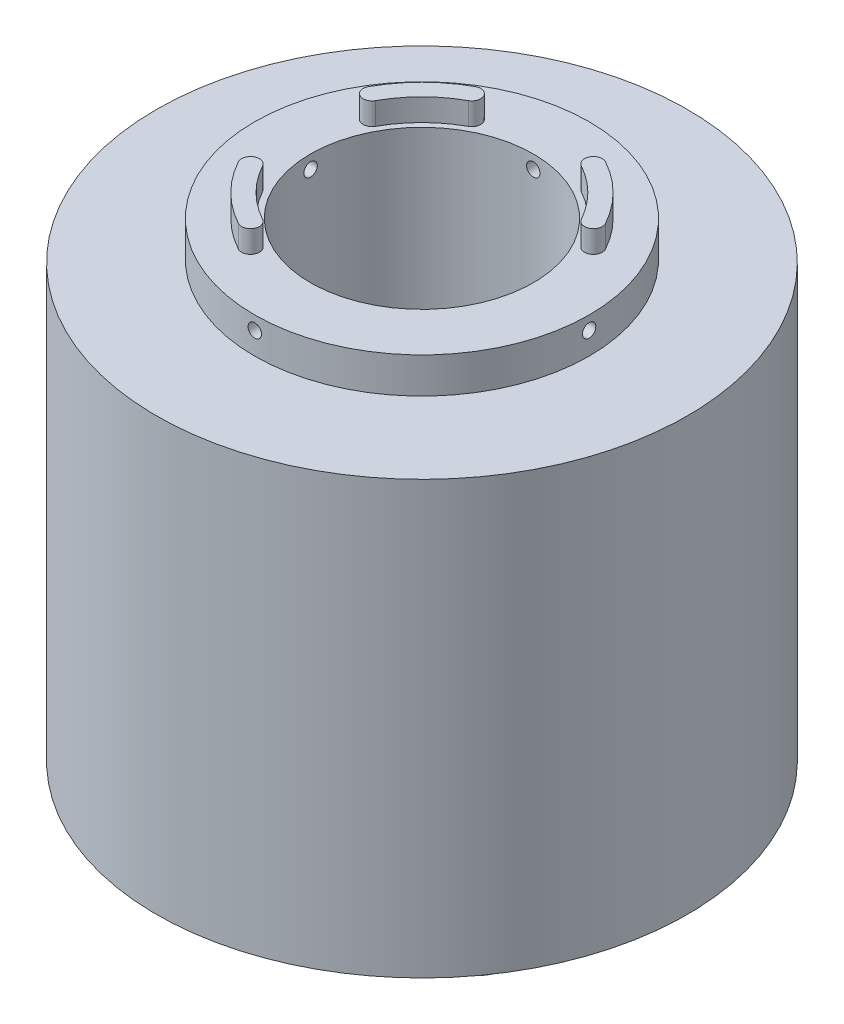
SolidWorks part; units mm, degrees
ref_plane "前视基准面" through (0, 0, 0) normal (0, 0, 1) x (1, 0, 0)
ref_plane "上视基准面" through (0, 0, 0) normal (0, 1, 0) x (1, 0, 0)
ref_plane "右视基准面" through (0, 0, 0) normal (1, 0, 0) x (0, 0, -1)
sketch "草图1" plane through (0, 0, 0) normal (0, 0, 1) x (1, 0, 0)
  line L0 (0, 57) -> (0, -48.4)
  line L1 (59.5, 48.4) -> (25, 48.4)
  line L2 (59.5, 48.4) -> (59.5, -48.4)
  line L3 (59.5, -48.4) -> (-59.5, -48.4)
  line L4 (-59.5, 48.4) -> (-59.5, -48.4)
  line L5 (59.5, 48.4) -> (-59.5, -48.4) construction
  line L6 (59.5, -48.4) -> (-59.5, 48.4) construction
  line L8 (25, 48.4) -> (25, -48.4)
  line L9 (25, -48.4) -> (-25, -48.4)
  line L10 (-25, 48.4) -> (-25, -48.4)
  line L11 (25, 48.4) -> (-25, -48.4) construction
  line L12 (25, -48.4) -> (-25, 48.4) construction
  line L13 (-25, 48.4) -> (-59.5, 48.4)
  line L18 (-37.5, 49) -> (37.5, 49)
  line L19 (-32.5, 49) -> (-32.5, 48.4)
  line L20 (37.5, 57) -> (-37.5, 57)
  line L21 (37.5, 57) -> (37.5, 49)
  line L23 (-37.5, 57) -> (-37.5, 49)
  line L24 (-25, 48.4) -> (-25, 57)
  point P0 (0, 0)
  point P5 (0, 0)
  dimension "D1" = 119
  dimension "D2" = 50
  dimension "D3" = 96.8
  dimension "D4" = 8.6
  dimension "D5" = 8
  dimension "D6" = 75
  dimension "D7" = 5
revolve "旋转1" add sketch "草图1" angle 360 about L0
sketch "草图3" plane through (0, 0, 0) normal (0, 0, 1) x (1, 0, 0)
  line L0 (37.5, 57) -> (-37.5, 57) construction
  circle A0 centre (0, 54) radius 1.5
  dimension "D1" = 3
  dimension "D2" = 3
extrude "切除-拉伸1" cut sketch "草图3" against normal through all
pattern_circular "阵列(圆周)1" count 4 over 360 about axis through (0, 57, 0) along (0, 1, 0) of "切除-拉伸1"
sketch "草图4" plane through (0, -48.4, 0) normal (0, -1, 0) x (1, 0, 0)
  line L5 (-0.4176, 62.7684) -> (0.2776, 64.3102) construction
  line L8 (0.2776, 64.3102) -> (0.4176, 62.7684) construction
  line L10 (63.47, 0) -> (-63.47, 0) construction
  line L19 (0, 59.5) -> (0, 0) construction
  circle A3 centre (-6.25, 51.75) radius 2
  circle A4 centre (0, 0) radius 59.5 construction
  circle A5 centre (6.25, 51.75) radius 2
  circle A6 centre (-6.25, -51.75) radius 2
  circle A7 centre (6.25, -51.75) radius 2
  point P0 (0.2776, 64.3102)
  dimension "D2" = 103.5
  dimension "D6" = 4
  dimension "D1" = 6.25
sketch "草图5" plane through (0, 57, 0) normal (0, 1, 0) x (1, 0, 0)
  line L0 (0, 0) -> (21.4253, 21.4253) construction
  line L2 (0, 0) -> (25, 0) construction
  line L3 (13.6295, 24.8018) -> (24.8018, 13.6295) construction
  arc A14 (14.5927, 26.5545) -> (26.5545, 14.5927) centre (0, 0) cw
  arc A15 (26.5545, 14.5927) -> (23.049, 12.6663) centre (24.8018, 13.6295) cw
  circle A19 centre (0, 0) radius 25 construction
  arc A33 (12.6663, 23.049) -> (14.5927, 26.5545) centre (13.6295, 24.8018) cw
  arc A34 (12.6663, 23.049) -> (23.049, 12.6663) centre (0, 0) cw
  arc A39 (-26.5545, -14.5927) -> (-23.049, -12.6663) centre (-24.8018, -13.6295) cw
  arc A40 (-14.5927, -26.5545) -> (-26.5545, -14.5927) centre (0, 0) cw
  arc A41 (-12.6663, -23.049) -> (-23.049, -12.6663) centre (0, 0) cw
  arc A42 (-12.6663, -23.049) -> (-14.5927, -26.5545) centre (-13.6295, -24.8018) cw
  arc A43 (-14.5927, 26.5545) -> (-12.6663, 23.049) centre (-13.6295, 24.8018) cw
  arc A44 (-26.5545, 14.5927) -> (-14.5927, 26.5545) centre (0, 0) cw
  arc A45 (-23.049, 12.6663) -> (-12.6663, 23.049) centre (0, 0) cw
  arc A46 (-23.049, 12.6663) -> (-26.5545, 14.5927) centre (-24.8018, 13.6295) cw
  arc A47 (14.5927, -26.5545) -> (12.6663, -23.049) centre (13.6295, -24.8018) cw [skipped]
  arc A48 (26.5545, -14.5927) -> (14.5927, -26.5545) centre (0, 0) cw [skipped]
  arc A49 (23.049, -12.6663) -> (12.6663, -23.049) centre (0, 0) cw [skipped]
  arc A50 (23.049, -12.6663) -> (26.5545, -14.5927) centre (24.8018, -13.6295) cw [skipped]
  point P6 (17.6777, 17.6777)
  point P11 (19.2156, 19.2156)
  point P35 (0, 0)
  point P37 (0, 0)
  dimension "D1" = 2
  dimension "D3" = 15.8
  dimension "D4" = 5.3
  dimension "D2" = 45
extrude "凸台-拉伸2" add sketch "草图5" along normal blind 5
sketch "草图6" plane through (0, -48.4, 0) normal (0, -1, 0) x (1, 0, 0)
  line L0 (40.6852, 27.5311) -> (44.1852, 21.4689) construction
  line L1 (43.7163, 29.2811) -> (47.2163, 23.2189)
  line L2 (37.6542, 25.7811) -> (41.1542, 19.7189)
  line L3 (0, 0) -> (-59.5, 0) construction
  line L4 (40.6852, -27.5311) -> (44.1852, -21.4689) construction
  line L5 (42.4352, 24.5) -> (0, 0) construction
  line L6 (43.7163, -29.2811) -> (47.2163, -23.2189)
  line L7 (37.6542, -25.7811) -> (41.1542, -19.7189)
  line L8 (0, -63.47) -> (0, 63.47) construction
  line L9 (-40.6852, -27.5311) -> (-44.1852, -21.4689) construction
  line L10 (-43.7163, -29.2811) -> (-47.2163, -23.2189)
  line L11 (-37.6542, -25.7811) -> (-41.1542, -19.7189)
  line L12 (-40.6852, 27.5311) -> (-44.1852, 21.4689) construction
  line L13 (-43.7163, 29.2811) -> (-47.2163, 23.2189)
  line L14 (-37.6542, 25.7811) -> (-41.1542, 19.7189)
  arc A0 (43.7163, 29.2811) -> (37.6542, 25.7811) centre (40.6852, 27.5311) ccw
  arc A1 (41.1542, 19.7189) -> (47.2163, 23.2189) centre (44.1852, 21.4689) ccw
  circle A2 centre (0, 0) radius 59.5 construction
  arc A4 (43.7163, -29.2811) -> (37.6542, -25.7811) centre (40.6852, -27.5311) cw
  arc A5 (41.1542, -19.7189) -> (47.2163, -23.2189) centre (44.1852, -21.4689) cw
  arc A6 (-43.7163, -29.2811) -> (-37.6542, -25.7811) centre (-40.6852, -27.5311) ccw
  arc A7 (-41.1542, -19.7189) -> (-47.2163, -23.2189) centre (-44.1852, -21.4689) ccw
  arc A8 (-43.7163, 29.2811) -> (-37.6542, 25.7811) centre (-40.6852, 27.5311) cw
  arc A9 (-41.1542, 19.7189) -> (-47.2163, 23.2189) centre (-44.1852, 21.4689) cw
  point P2 (42.4352, 24.5)
  point P20 (42.4352, -24.5)
  point P29 (-42.4352, -24.5)
  point P36 (-42.4352, 24.5)
  dimension "D2" = 3.5
  dimension "D1" = 7
  dimension "D3" = 49
  dimension "D4" = 30
extrude "凸台-拉伸3" add sketch "草图6" along normal blind 5
extrude "切除-拉伸2" cut sketch "草图4" against normal blind 8
sketch "草图7" plane through (0, -48.4, 0) normal (0, -1, 0) x (1, 0, 0)
  line L0 (9.75, -45) -> (9.75, -78)
  line L1 (-9.75, 78) -> (-4.75, 78)
  line L2 (-9.75, 78) -> (-9.75, 45)
  line L3 (-9.75, -78) -> (-4.75, -78)
  line L4 (9.75, 78) -> (9.75, 45)
  line L5 (-9.75, 78) -> (-5.625, 45) construction
  line L6 (-9.75, -78) -> (-5.625, -45) construction
  line L7 (-9.75, 45) -> (9.75, 45)
  line L9 (-9.75, -45) -> (9.75, -45)
  line L11 (0, 67.5) -> (0, -67.5) construction
  line L12 (-4.75, -67.5) -> (-4.75, -78)
  line L13 (5.625, 45) -> (9.75, 78) construction
  line L14 (5.625, -45) -> (9.75, -78) construction
  line L15 (-9.75, -45) -> (-9.75, -78)
  line L16 (4.75, -67.5) -> (4.75, -78)
  line L17 (-4.75, 67.5) -> (-4.75, 78)
  line L18 (4.75, 67.5) -> (4.75, 78)
  line L19 (4.75, 78) -> (9.75, 78)
  line L20 (4.75, -78) -> (9.75, -78)
  arc A0 (-4.75, 67.5) -> (4.75, 67.5) centre (0, 67.5) ccw
  arc A1 (4.75, -67.5) -> (-4.75, -67.5) centre (0, -67.5) ccw
  point P0 (0, 0)
  point P6 (0, 0)
  dimension "D7" = 9.5
  dimension "D8" = 9.5
  dimension "D1" = 19.5
  dimension "D2" = 78
  dimension "D3" = 90
  dimension "D4" = 45
  dimension "D5" = 67.5
  dimension "D6" = 135
extrude "凸台-拉伸4" [suppressed] add sketch "草图7" along normal blind 4
